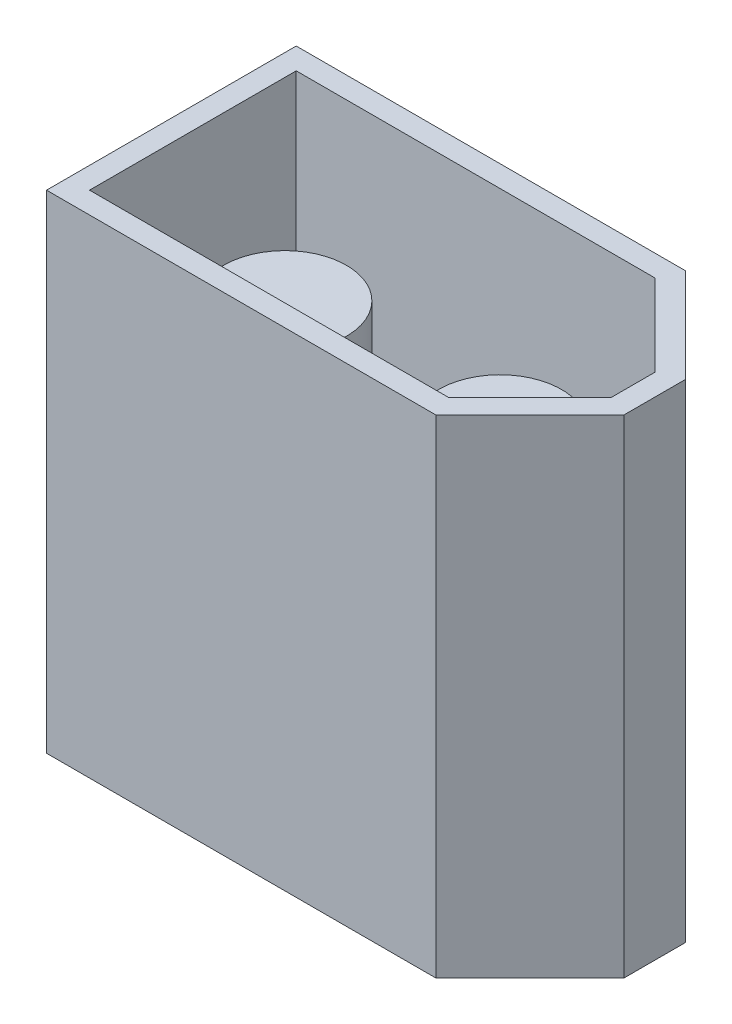
SolidWorks part; units mm, degrees
ref_plane "Přední rovina" through (0, 0, 0) normal (0, 0, 1) x (1, 0, 0)
ref_plane "Horní rovina" through (0, 0, 0) normal (0, 1, 0) x (1, 0, 0)
ref_plane "Pravá rovina" through (0, 0, 0) normal (1, 0, 0) x (0, 0, -1)
sketch "Skica1" plane through (0, 0, 0) normal (0, 1, 0) x (1, 0, 0)
  line L0 (-7.8677, 4.064) -> (-7.8677, -4.064)
  line L1 (-7.8677, -4.064) -> (4.8037, -4.064)
  line L2 (4.8037, -4.064) -> (7.8677, -1)
  line L3 (7.8677, -1) -> (7.8677, 1)
  line L4 (-7.8676, 0) -> (7.8676, 0) construction
  line L5 (4.8037, 4.064) -> (7.8677, 1)
  line L6 (-7.8677, 4.064) -> (4.8037, 4.064)
  dimension "D1" = 15.7353
  dimension "D2" = 8.128
  dimension "D3" = 45
  dimension "D4" = 2
extrude "Přidat vysunutím1" add sketch "Skica1" along normal blind 15.875
shell "Skořepina1" thickness 0.7
sketch "Skica2" plane through (0, 0.7, 0) normal (0, 1, 0) x (1, 0, 0)
  line L0 (-4.1677, 0) -> (2.8323, 0) construction
  line L1 (-7.1677, 3.364) -> (-7.1677, -3.364) construction
  circle A0 centre (-4.1677, 0) radius 2
  circle A1 centre (2.8323, 0) radius 2
  dimension "D1" = 7
  dimension "D2" = 4
  dimension "D3" = 3
extrude "Přidat vysunutím2" add sketch "Skica2" along normal blind 11.875 and the other way blind 2 separate body
